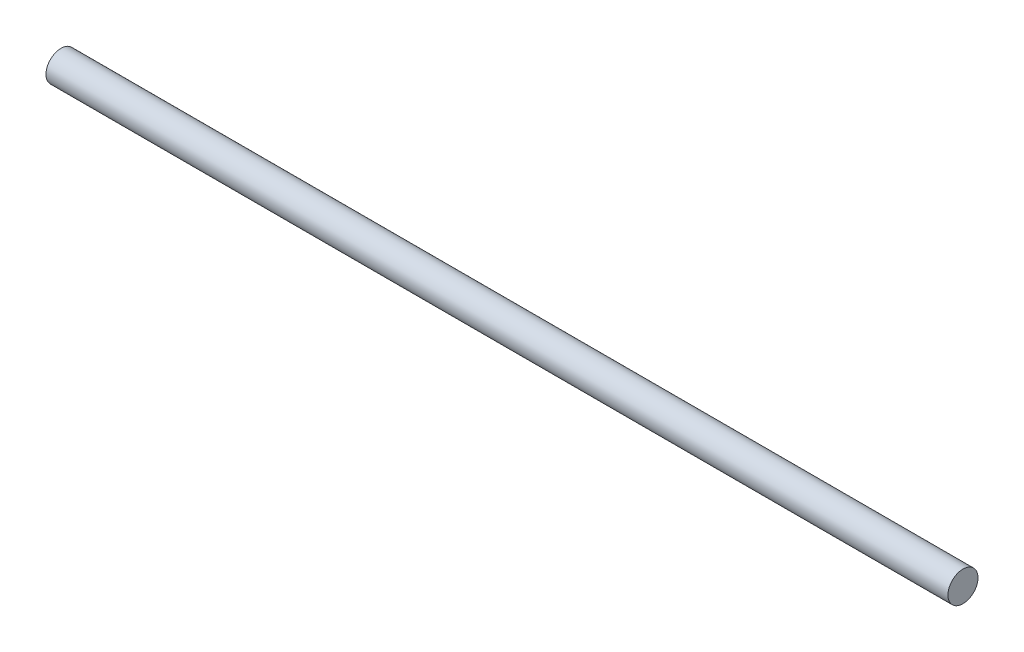
SolidWorks part; units mm, degrees
ref_plane "Front Plane" through (0, 0, 0) normal (0, 0, 1) x (1, 0, 0)
ref_plane "Top Plane" through (0, 0, 0) normal (0, 1, 0) x (1, 0, 0)
ref_plane "Right Plane" through (0, 0, 0) normal (1, 0, 0) x (0, 0, -1)
sketch "Sketch2" plane through (0, 0, 0) normal (1, 0, 0) x (0, 0, -1)
  circle A0 centre (0, 0) radius 2.5
  dimension "D1" = 5
extrude "Boss-Extrude1" add sketch "Sketch2" along normal blind 150
